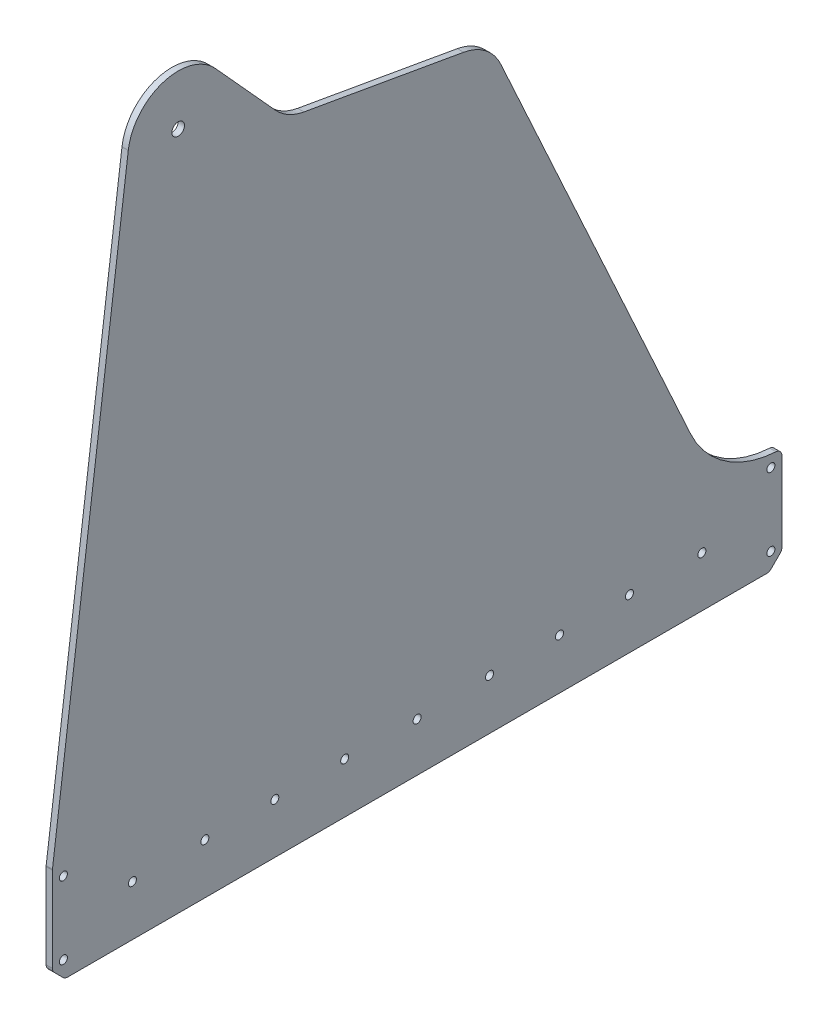
SolidWorks part; units mm, degrees
ref_plane "Front Plane" through (0, 0, 0) normal (0, 0, 1) x (1, 0, 0)
ref_plane "Top Plane" through (0, 0, 0) normal (0, 1, 0) x (1, 0, 0)
ref_plane "Right Plane" through (0, 0, 0) normal (1, 0, 0) x (0, 0, -1)
sketch "Sketch2" plane through (0, 0, 0) normal (1, 0, 0) x (0, 0, -1)
  line L0 (0, 0) -> (0, 50.8)
  line L1 (0, 50.8) -> (38.311, 346.1672)
  line L4 (368.3, 50.8) -> (368.3, 0)
  line L5 (368.3, 0) -> (0, 0)
  line L7 (226.2992, 289.9635) -> (322.1016, 80.473)
  line L8 (368.3, 50.8) -> (419.4553, 50.8) construction
  line L9 (0, 374.65) -> (368.3, 374.65) construction
  line L10 (82.3138, 359.9646) -> (112.5969, 326.5774)
  line L11 (127, 318.628) -> (207.6107, 304.4141)
  arc A0 (38.311, 346.1672) -> (82.3138, 359.9646) centre (63.5, 342.9) cw
  arc A1 (207.6107, 304.4141) -> (226.2992, 289.9635) centre (203.2, 279.4) cw
  arc A2 (322.1016, 80.473) -> (368.3, 50.8) centre (368.3, 101.6) ccw
  arc A3 (112.5969, 326.5774) -> (127, 318.628) centre (131.4107, 343.6421) ccw
  point P19 (102.2936, 338.7052)
  point P20 (130.4478, 355.6)
  point P21 (110.4546, 336.2653)
  point P22 (206.0251, 330.0424)
  dimension "D6" = 25.4
  dimension "D3" = 50.8
  dimension "D7" = 25.4
  dimension "D1" = 368.3
  dimension "D2" = 50.8
  dimension "D4" = 304.8
  dimension "D5" = 342.9
  dimension "D8" = 374.65
  dimension "D9" = 279.4
  dimension "D10" = 203.2
  dimension "D11" = 127
  dimension "D12" = 10
extrude "Plate" add sketch "Sketch2" along normal blind 3.175
sketch "Sketch4" plane through (3.175, 0, 0) normal (1, 0, 0) x (0, 0, -1)
  line L4 (184.15, 24.6062) -> (220.7174, 25.4) construction
  line L7 (220.7174, 25.4) -> (256.0234, 25.4) construction
  line L8 (256.0234, 25.4) -> (291.3294, 25.4) construction
  line L9 (291.3294, 25.4) -> (327.9054, 25.4) construction
  line L12 (184.15, 24.6062) -> (147.5826, 25.4) construction
  line L13 (147.5826, 25.4) -> (112.2766, 25.4) construction
  line L14 (112.2766, 25.4) -> (76.9706, 25.4) construction
  line L15 (76.9706, 25.4) -> (40.3946, 25.4) construction
  line L18 (0, 0) -> (368.3, 0) construction
  line L19 (368.3, 0) -> (368.3, 50.8) construction
  point P0 (184.15, 24.6062)
  point P10 (220.7174, 25.4)
  point P12 (256.0234, 25.4)
  point P14 (291.3294, 25.4)
  point P16 (327.9054, 25.4)
  point P18 (147.5826, 25.4)
  point P20 (112.2766, 25.4)
  point P22 (76.9706, 25.4)
  point P24 (40.3946, 25.4)
  point P50 (184.15, 0)
  point P54 (368.3, 25.4)
  dimension "Small-Large Gear Spacing" = 36.576
  dimension "Small to Small Hole Spacing" = 35.306
  dimension "D1" = 287.5108
  dimension "D2" = 0.7937
hole_wizard "Drive Holes" positions "Sketch4" profile "Sketch6" hole size "#8" standard "ANSI Inch" end condition through all
sketch "Sketch6" plane through (3.175, 24.6062, -184.15) normal (0, 1, 0) x (0, 0, -1)
  line L0 (0, 0) -> (0, 3.175)
  line L1 (0, 3.175) -> (2.032, 3.175)
  line L2 (2.032, 3.175) -> (2.032, 0)
  line L5 (2.032, 0) -> (0, 0)
  line L11 (0, -6.35) -> (0, 107.95) construction
  dimension "Thru Hole Dia." = 4.064
  dimension "Thru Hole Depth" = 3.175
sketch "Sketch3" plane through (3.175, 0, 0) normal (1, 0, 0) x (0, 0, -1)
  circle A0 centre (63.5, 342.9) radius 3.175
  dimension "D1" = 6.35
extrude "Tube Pivot Holes" cut sketch "Sketch3" against normal through all
chamfer "Bottom Corner Chamfer" distance 6.35 angle 45 2 edges at (1.5875, 0, -368.3) (1.5875, 0, 0)
fillet "Bottom Corner Fillet" radius 3.175 6 edges at (1.5875, 50.8, 0) (1.5875, 0, -6.35) (1.5875, 6.35, 0) (1.5875, 0, -361.95) (1.5875, 6.35, -368.3) (1.5875, 50.8, -368.3)
sketch "Sketch7" plane through (3.175, 0, 0) normal (1, 0, 0) x (0, 0, -1)
  point P0 (5.5562, 45.2438)
  point P1 (5.5562, 8.6515)
  point P3 (362.7438, 45.2438)
  point P5 (362.7438, 8.6515)
hole_wizard "Carbon Cap Holes" positions "Sketch7" profile "Sketch8" hole size "#8" standard "ANSI Inch" end condition through all
sketch "Sketch8" plane through (3.175, 45.2438, -5.5562) normal (0, 1, 0) x (0, 0, -1)
  line L0 (0, 0) -> (0, 3.175)
  line L1 (0, 3.175) -> (2.032, 3.175)
  line L2 (2.032, 3.175) -> (2.032, 0)
  line L5 (2.032, 0) -> (0, 0)
  line L11 (0, -6.35) -> (0, 107.95) construction
  dimension "Thru Hole Dia." = 4.064
  dimension "Thru Hole Depth" = 3.175
equation "\"Small to Small Gear Spacing\"= ( 28 / 20 ) - .01"
equation "\"Small to Big Gear Spacing\"= ( 28 / 40 ) + ( 30 / 40 ) - .01"
equation "\"Small-Large Gear Spacing@Sketch4\"= \"Small to Big Gear Spacing\""
equation "\"Small to Small Hole Spacing@Sketch4\"= \"Small to Small Gear Spacing\""
